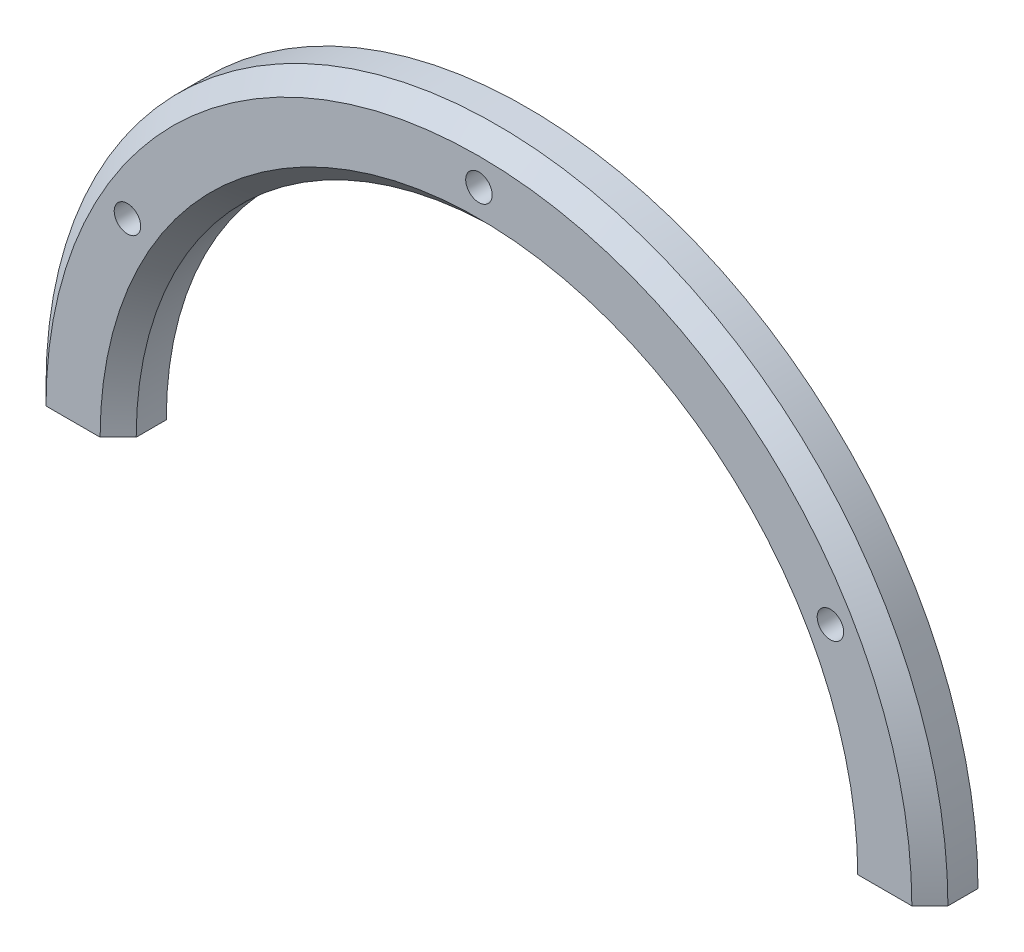
SolidWorks part; units mm, degrees
ref_plane "Alzado" through (0, 0, 0) normal (0, 0, 1) x (1, 0, 0)
ref_plane "Planta" through (0, 0, 0) normal (0, 1, 0) x (1, 0, 0)
ref_plane "Vista lateral" through (0, 0, 0) normal (1, 0, 0) x (0, 0, -1)
sketch "Croquis1" plane through (0, 0, 0) normal (0, 0, 1) x (1, 0, 0)
  line L0 (-75, 0) -> (-60, 0)
  line L7 (60, 0) -> (75, 0)
  circle A2 centre (0, 67.5) radius 2.2
  circle A3 centre (-58.4567, 33.75) radius 2.2
  circle A7 centre (58.4567, 33.75) radius 2.2
  arc A9 (75, 0) -> (-75, 0) centre (0, 0) ccw
  arc A10 (60, 0) -> (-60, 0) centre (0, 0) ccw
extrude "Saliente-Extruir1" add sketch "Croquis1" along normal blind 8
chamfer "Chaflán1" distance 3 angle 45 2 edges at (0, 60, 8) (0, 75, 8)
